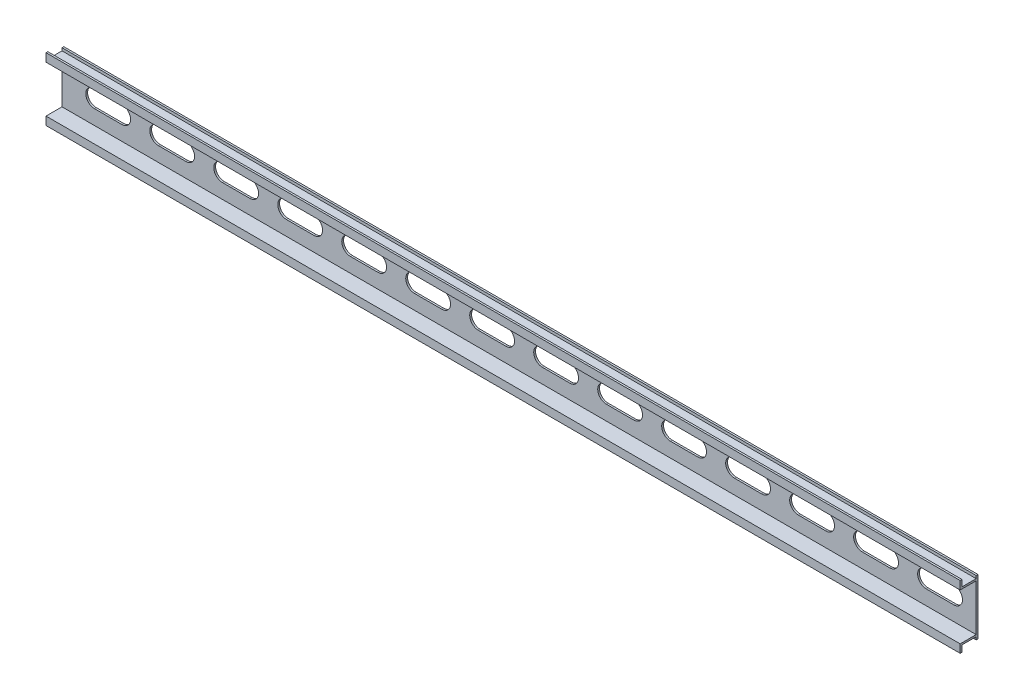
SolidWorks part; units mm, degrees
ref_plane "Front Plane" through (0, 0, 0) normal (0, 0, 1) x (1, 0, 0)
ref_plane "Top Plane" through (0, 0, 0) normal (0, 1, 0) x (1, 0, 0)
ref_plane "Right Plane" through (0, 0, 0) normal (1, 0, 0) x (0, 0, -1)
sketch "Sketch1" plane through (0, 0, 0) normal (1, 0, 0) x (0, 0, -1)
  line L0 (0, 0) -> (96.2341, 0) construction
  line L1 (0, 12.954) -> (0, -12.954)
  line L2 (0, -12.954) -> (-8.89, -12.954)
  line L3 (-8.89, -12.954) -> (-8.89, -17.526)
  line L4 (-8.89, -17.526) -> (-7.874, -17.526)
  line L5 (-7.874, -17.526) -> (-7.874, -13.97)
  line L6 (-7.874, -13.97) -> (0, -13.97)
  line L7 (0, -13.97) -> (0, -15.494)
  line L8 (0, -15.494) -> (1.016, -15.494)
  line L9 (1.016, -15.494) -> (1.016, 15.494)
  line L10 (-7.874, 17.526) -> (-7.874, 13.97)
  line L11 (-8.89, 17.526) -> (-7.874, 17.526)
  line L12 (-8.89, 12.954) -> (-8.89, 17.526)
  line L13 (0, 12.954) -> (-8.89, 12.954)
  line L14 (-7.874, 13.97) -> (0, 13.97)
  line L15 (0, 15.494) -> (1.016, 15.494)
  line L16 (0, 13.97) -> (0, 15.494)
  point P20 (1.016, 0)
  dimension "D1" = 96.2341
  dimension "D2" = 25.908
  dimension "D3" = 9.906
  dimension "D4" = 1.016
  dimension "D5" = 1.016
  dimension "D6" = 1.016
  dimension "D7" = 30.988
  dimension "D8" = 1.016
  dimension "D9" = 35.052
extrude "Boss-Extrude1" add sketch "Sketch1" along normal blind 508
sketch "Sketch2" plane through (0, 0, -1.016) normal (0, 0, -1) x (-1, 0, 0)
  line L0 (-495.554, 0) -> (-480.314, 0) construction
  line L1 (-495.554, 4.826) -> (-480.314, 4.826)
  line L2 (-495.554, -4.826) -> (-480.314, -4.826)
  line L3 (-508, -15.494) -> (-508, 15.494) construction
  line L4 (-459.994, 0) -> (-444.754, 0) construction
  line L5 (-459.994, 4.826) -> (-444.754, 4.826)
  line L6 (-459.994, -4.826) -> (-444.754, -4.826)
  line L7 (-424.434, 0) -> (-409.194, 0) construction
  line L8 (-424.434, 4.826) -> (-409.194, 4.826)
  line L9 (-424.434, -4.826) -> (-409.194, -4.826)
  line L10 (-388.874, 0) -> (-373.634, 0) construction
  line L11 (-388.874, 4.826) -> (-373.634, 4.826)
  line L12 (-388.874, -4.826) -> (-373.634, -4.826)
  line L13 (-353.314, 0) -> (-338.074, 0) construction
  line L14 (-353.314, 4.826) -> (-338.074, 4.826)
  line L15 (-353.314, -4.826) -> (-338.074, -4.826)
  line L16 (-317.754, 0) -> (-302.514, 0) construction
  line L17 (-317.754, 4.826) -> (-302.514, 4.826)
  line L18 (-317.754, -4.826) -> (-302.514, -4.826)
  line L19 (-282.194, 0) -> (-266.954, 0) construction
  line L20 (-282.194, 4.826) -> (-266.954, 4.826)
  line L21 (-282.194, -4.826) -> (-266.954, -4.826)
  line L22 (-246.634, 0) -> (-231.394, 0) construction
  line L23 (-246.634, 4.826) -> (-231.394, 4.826)
  line L24 (-246.634, -4.826) -> (-231.394, -4.826)
  line L25 (-211.074, 0) -> (-195.834, 0) construction
  line L26 (-211.074, 4.826) -> (-195.834, 4.826)
  line L27 (-211.074, -4.826) -> (-195.834, -4.826)
  line L28 (-175.514, 0) -> (-160.274, 0) construction
  line L29 (-175.514, 4.826) -> (-160.274, 4.826)
  line L30 (-175.514, -4.826) -> (-160.274, -4.826)
  line L31 (-139.954, 0) -> (-124.714, 0) construction
  line L32 (-139.954, 4.826) -> (-124.714, 4.826)
  line L33 (-139.954, -4.826) -> (-124.714, -4.826)
  line L34 (-104.394, 0) -> (-89.154, 0) construction
  line L35 (-104.394, 4.826) -> (-89.154, 4.826)
  line L36 (-104.394, -4.826) -> (-89.154, -4.826)
  line L37 (-68.834, 0) -> (-53.594, 0) construction
  line L38 (-68.834, 4.826) -> (-53.594, 4.826)
  line L39 (-68.834, -4.826) -> (-53.594, -4.826)
  line L40 (-33.274, 0) -> (-18.034, 0) construction
  line L41 (-33.274, 4.826) -> (-18.034, 4.826)
  line L42 (-33.274, -4.826) -> (-18.034, -4.826)
  line L43 (0, -15.494) -> (0, 15.494) construction
  arc A0 (-495.554, 4.826) -> (-495.554, -4.826) centre (-495.554, 0) ccw
  arc A1 (-480.314, -4.826) -> (-480.314, 4.826) centre (-480.314, 0) ccw
  arc A2 (-459.994, 4.826) -> (-459.994, -4.826) centre (-459.994, 0) ccw
  arc A3 (-444.754, -4.826) -> (-444.754, 4.826) centre (-444.754, 0) ccw
  arc A4 (-424.434, 4.826) -> (-424.434, -4.826) centre (-424.434, 0) ccw
  arc A5 (-409.194, -4.826) -> (-409.194, 4.826) centre (-409.194, 0) ccw
  arc A6 (-388.874, 4.826) -> (-388.874, -4.826) centre (-388.874, 0) ccw
  arc A7 (-373.634, -4.826) -> (-373.634, 4.826) centre (-373.634, 0) ccw
  arc A8 (-353.314, 4.826) -> (-353.314, -4.826) centre (-353.314, 0) ccw
  arc A9 (-338.074, -4.826) -> (-338.074, 4.826) centre (-338.074, 0) ccw
  arc A10 (-317.754, 4.826) -> (-317.754, -4.826) centre (-317.754, 0) ccw
  arc A11 (-302.514, -4.826) -> (-302.514, 4.826) centre (-302.514, 0) ccw
  arc A12 (-282.194, 4.826) -> (-282.194, -4.826) centre (-282.194, 0) ccw
  arc A13 (-266.954, -4.826) -> (-266.954, 4.826) centre (-266.954, 0) ccw
  arc A14 (-246.634, 4.826) -> (-246.634, -4.826) centre (-246.634, 0) ccw
  arc A15 (-231.394, -4.826) -> (-231.394, 4.826) centre (-231.394, 0) ccw
  arc A16 (-211.074, 4.826) -> (-211.074, -4.826) centre (-211.074, 0) ccw
  arc A17 (-195.834, -4.826) -> (-195.834, 4.826) centre (-195.834, 0) ccw
  arc A18 (-175.514, 4.826) -> (-175.514, -4.826) centre (-175.514, 0) ccw
  arc A19 (-160.274, -4.826) -> (-160.274, 4.826) centre (-160.274, 0) ccw
  arc A20 (-139.954, 4.826) -> (-139.954, -4.826) centre (-139.954, 0) ccw
  arc A21 (-124.714, -4.826) -> (-124.714, 4.826) centre (-124.714, 0) ccw
  arc A22 (-104.394, 4.826) -> (-104.394, -4.826) centre (-104.394, 0) ccw
  arc A23 (-89.154, -4.826) -> (-89.154, 4.826) centre (-89.154, 0) ccw
  arc A24 (-68.834, 4.826) -> (-68.834, -4.826) centre (-68.834, 0) ccw
  arc A25 (-53.594, -4.826) -> (-53.594, 4.826) centre (-53.594, 0) ccw
  arc A26 (-33.274, 4.826) -> (-33.274, -4.826) centre (-33.274, 0) ccw
  arc A27 (-18.034, -4.826) -> (-18.034, 4.826) centre (-18.034, 0) ccw
  point P3 (-487.934, 0)
  point P8 (-500.38, 0)
  point P9 (-475.488, 0)
  point P15 (-452.374, 0)
  point P22 (-416.814, 0)
  point P29 (-381.254, 0)
  point P36 (-345.694, 0)
  point P43 (-310.134, 0)
  point P50 (-274.574, 0)
  point P57 (-239.014, 0)
  point P64 (-203.454, 0)
  point P71 (-167.894, 0)
  point P78 (-132.334, 0)
  point P85 (-96.774, 0)
  point P92 (-61.214, 0)
  point P99 (-25.654, 0)
  dimension "D1" = 4.826
  dimension "D2" = 24.892
  dimension "D3" = 20.066
  dimension "D5" = 18.034
  dimension "D4" = 14
extrude "Cut-Extrude1" cut sketch "Sketch2" against normal through all
